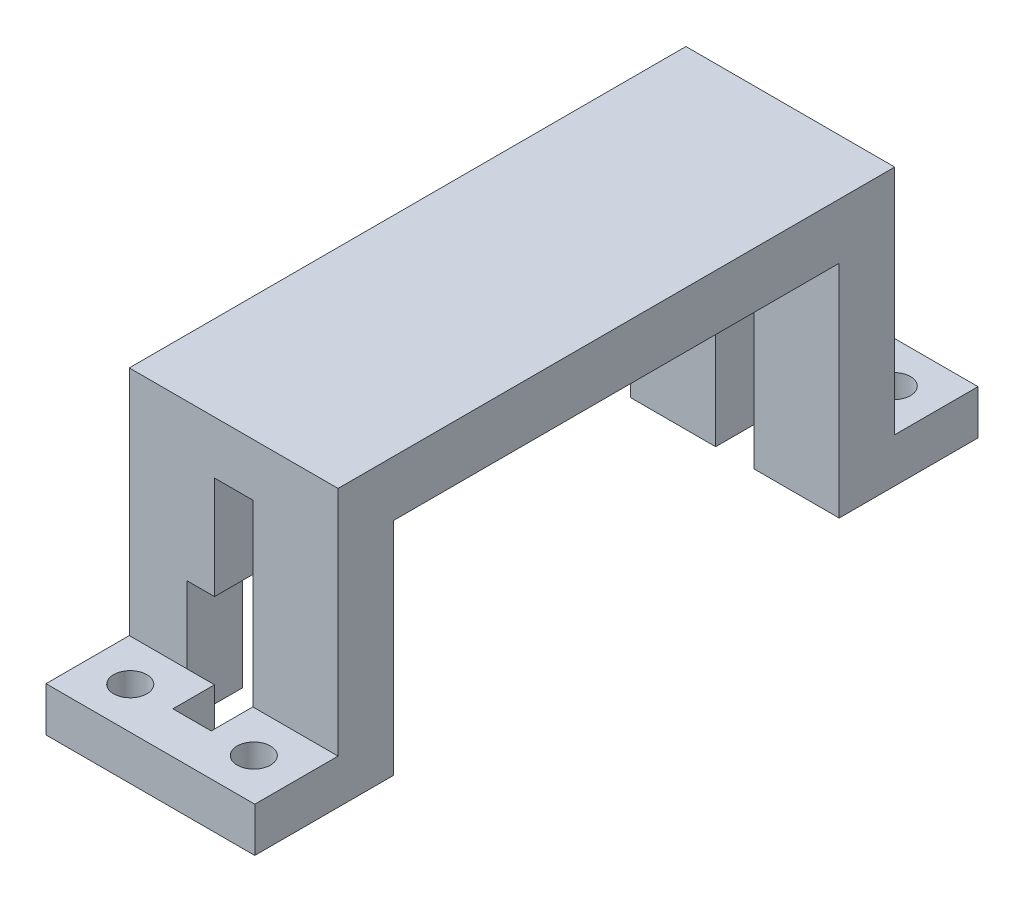
SolidWorks part; units mm, degrees
ref_plane "Front Plane" through (0, 0, 0) normal (0, 0, 1) x (1, 0, 0)
ref_plane "Top Plane" through (0, 0, 0) normal (0, 1, 0) x (1, 0, 0)
ref_plane "Right Plane" through (0, 0, 0) normal (1, 0, 0) x (0, 0, -1)
sketch "Sketch1" plane through (0, 0, 0) normal (1, 0, 0) x (0, 0, -1)
  line L0 (-25.0625, 0) -> (25.0625, 0)
  line L1 (-25.0625, 0) -> (-25.0625, -20.875)
  line L2 (-25.0625, -24.875) -> (-20.0625, -24.875)
  line L3 (-20.0625, -24.875) -> (-20.0625, -5)
  line L4 (-20.0625, -5) -> (20.0625, -5)
  line L5 (20.0625, -5) -> (20.0625, -24.875)
  line L6 (20.0625, -24.875) -> (25.0625, -24.875)
  line L7 (25.0625, -20.875) -> (25.0625, 0)
  line L8 (-20.0625, 0) -> (-20.0625, -5) construction
  line L10 (-25.0625, -24.875) -> (-32.5625, -24.875)
  line L12 (-25.0625, -20.875) -> (-32.5625, -20.875)
  line L13 (-32.5625, -24.875) -> (-32.5625, -20.875)
  line L14 (25.0625, -24.875) -> (32.5625, -24.875)
  line L16 (25.0625, -20.875) -> (32.5625, -20.875)
  line L17 (32.5625, -24.875) -> (32.5625, -20.875)
  point P4 (0, 0)
  dimension "D1" = 40.125
  dimension "D2" = 19.875
  dimension "D3" = 5
  dimension "D4" = 4
  dimension "D5" = 7.5
extrude "Boss-Extrude1" add sketch "Sketch1" along normal blind 18.8
sketch "Sketch2" plane through (0, 0, 32.5625) normal (0, 0, 1) x (1, 0, 0)
  line L0 (0, -24.875) -> (7.675, -24.875) construction
  line L1 (18.8, -24.875) -> (0, -24.875) construction
  line L2 (7.675, -24.875) -> (7.675, -4.75)
  line L3 (7.675, -4.75) -> (11.125, -4.75)
  line L4 (11.125, -4.75) -> (11.125, -24.875)
  line L5 (11.125, -24.875) -> (7.675, -24.875)
  dimension "D1" = 7.675
  dimension "D2" = 3.45
  dimension "D3" = 20.125
extrude "Cut-Extrude1" cut sketch "Sketch2" against normal through all
sketch "Sketch3" plane through (0, -20.875, 0) normal (0, 1, 0) x (1, 0, 0)
  line L0 (2.7647, -27.7641) -> (4.9103, -29.8609) construction
  line L1 (4.9103, -27.7641) -> (2.7647, -29.8609) construction
  line L2 (13.8897, -27.7641) -> (16.0353, -29.8609) construction
  line L3 (16.0353, -27.7641) -> (13.8897, -29.8609) construction
  line L4 (2.7647, 29.8609) -> (4.9103, 27.7641) construction
  line L5 (2.7647, 27.7641) -> (4.9103, 29.8609) construction
  line L6 (13.8897, 29.8609) -> (16.0353, 27.7641) construction
  line L7 (16.0353, 29.8609) -> (13.8897, 27.7641) construction
  circle A0 centre (3.8375, -28.8125) radius 1.5
  circle A2 centre (14.9625, -28.8125) radius 1.5
  circle A3 centre (14.9625, 28.8125) radius 1.5
  circle A4 centre (3.8375, 28.8125) radius 1.5
  dimension "D1" = 2
  dimension "D2" = 2
extrude "Cut-Extrude2" cut sketch "Sketch3" against normal up to next contours A0 | A2 | A3 | A4
sketch "Sketch4" plane through (7.675, 0, 0) normal (1, 0, 0) x (0, 0, -1)
  line L0 (-20.0625, -24.875) -> (-20.0625, -15.75)
  line L1 (-20.0625, -24.875) -> (-20.0625, -5) construction
  line L2 (-20.0625, -15.75) -> (-20.0625, -14)
  line L3 (-20.0625, -14) -> (-25.0625, -14)
  line L4 (-25.0625, 0) -> (-25.0625, -20.875) construction
  line L5 (-25.0625, -14) -> (-25.0625, -15.75)
  line L7 (-25.0625, -15.75) -> (-25.0625, -24.875)
  line L8 (-32.5625, -24.875) -> (-20.0625, -24.875) construction
  line L9 (-25.0625, -24.875) -> (-20.0625, -24.875)
  dimension "D1" = 9.125
  dimension "D2" = 1.75
sketch "Sketch7" plane through (7.675, 0, 0) normal (1, 0, 0) x (0, 0, -1)
  line L0 (-32.5625, -24.875) -> (-20.0625, -24.875) construction
  line L2 (-32.5625, -20.875) -> (-28.8125, -20.875)
  line L3 (-32.5625, -20.875) -> (-32.5625, -24.875)
  line L4 (-32.5625, -24.875) -> (-28.8125, -24.875)
  line L5 (-28.8125, -20.875) -> (-28.8125, -24.875)
  line L6 (-27.3125, -20.875) -> (-30.3125, -20.875) construction
extrude "Boss-Extrude2" add sketch "Sketch7" along normal up to next
mirror "Mirror1" about plane through (0, 0, 0) normal (0, 0, 1) of "Boss-Extrude2"
extrude "Cut-Extrude8" cut sketch "Sketch4" against normal blind 2.5
